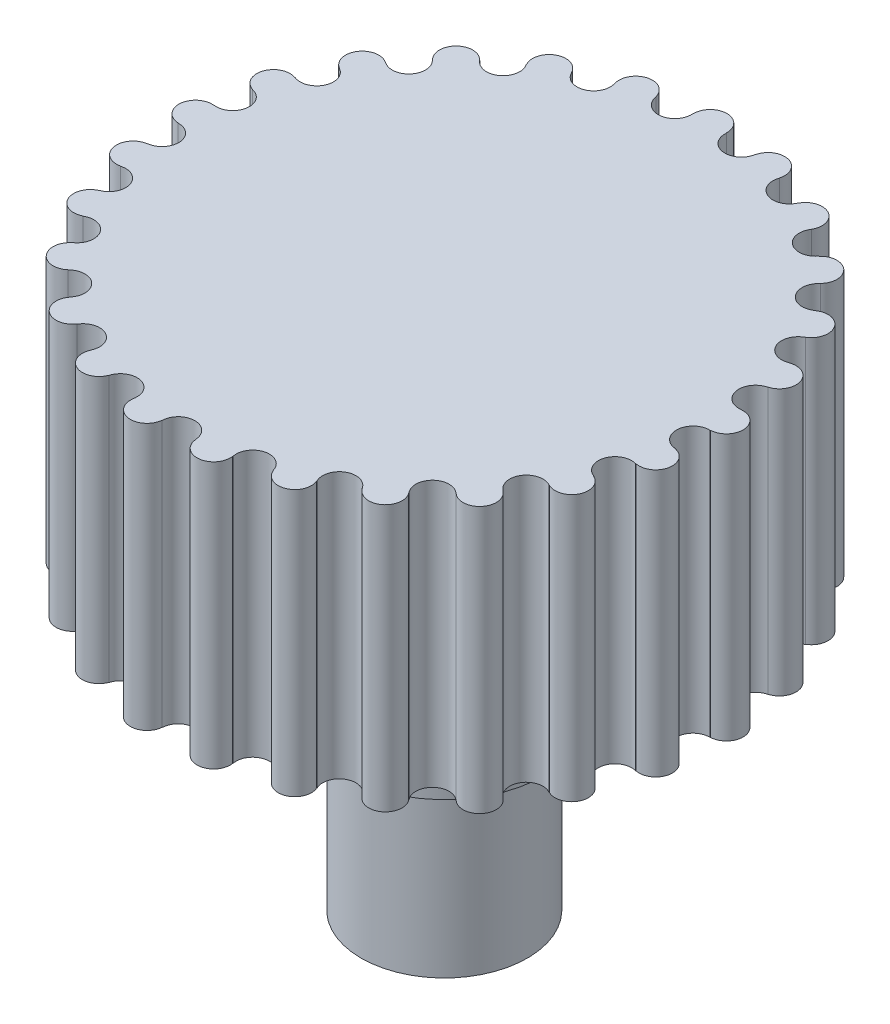
SolidWorks part; units mm, degrees
ref_plane "前视基准面" through (0, 0, 0) normal (0, 0, 1) x (1, 0, 0)
ref_plane "上视基准面" through (0, 0, 0) normal (0, 1, 0) x (1, 0, 0)
ref_plane "右视基准面" through (0, 0, 0) normal (1, 0, 0) x (0, 0, -1)
other "Configuration Table"
sketch "草图1" plane through (0, 0, 0) normal (0, 1, 0) x (1, 0, 0)
  circle A0 centre (0, 0) radius 2.5
extrude "凸台-拉伸1" add sketch "草图1" along normal blind 6
sketch "草图2" plane through (0, 6, 0) normal (0, 1, 0) x (1, 0, 0)
  circle A0 centre (0, 0) radius 3
extrude "凸台-拉伸2" add sketch "草图2" against normal blind 1
sketch "草图3" plane through (0, 6, 0) normal (0, 1, 0) x (1, 0, 0)
  circle A0 centre (0, 0) radius 2.5
extrude "凸台-拉伸3" add sketch "草图3" along normal blind 2.5
sketch "草图4" plane through (0, 8.5, 0) normal (0, 1, 0) x (1, 0, 0)
  circle A0 centre (0, 0) radius 8
extrude "凸台-拉伸4" add sketch "草图4" along normal blind 8
sketch "草图6" plane through (0, 16.5, 0) normal (0, 1, 0) x (1, 0, 0)
  circle A0 centre (0, 8) radius 0.5
  circle A1 centre (0, 0) radius 8 construction
  circle A3 centre (1.9895, 7.7487) radius 0.5
  circle A5 centre (3.854, 7.0105) radius 0.5
  circle A7 centre (5.4764, 5.8317) radius 0.5
  circle A9 centre (6.7546, 4.2866) radius 0.5
  circle A11 centre (7.6085, 2.4721) radius 0.5
  circle A13 centre (7.9842, 0.5023) radius 0.5
  circle A15 centre (7.8583, -1.4991) radius 0.5
  circle A17 centre (7.2386, -3.4062) radius 0.5
  circle A19 centre (6.1641, -5.0994) radius 0.5
  circle A21 centre (4.7023, -6.4721) radius 0.5
  circle A23 centre (2.945, -7.4382) radius 0.5
  circle A25 centre (1.0027, -7.9369) radius 0.5
  circle A27 centre (-1.0027, -7.9369) radius 0.5
  circle A29 centre (-2.945, -7.4382) radius 0.5
  circle A31 centre (-4.7023, -6.4721) radius 0.5
  circle A33 centre (-6.1641, -5.0994) radius 0.5
  circle A35 centre (-7.2386, -3.4062) radius 0.5
  circle A37 centre (-7.8583, -1.4991) radius 0.5
  circle A39 centre (-7.9842, 0.5023) radius 0.5
  circle A41 centre (-7.6085, 2.4721) radius 0.5
  circle A43 centre (-6.7546, 4.2866) radius 0.5
  circle A45 centre (-5.4764, 5.8317) radius 0.5
  circle A47 centre (-3.854, 7.0105) radius 0.5
  circle A49 centre (-1.9895, 7.7487) radius 0.5
  circle A51 centre (1.0027, 7.9369) radius 0.5 [skipped]
  circle A52 centre (2.945, 7.4382) radius 0.5 [skipped]
  circle A53 centre (4.7023, 6.4721) radius 0.5 [skipped]
  circle A54 centre (6.1641, 5.0994) radius 0.5 [skipped]
  circle A55 centre (7.2386, 3.4062) radius 0.5 [skipped]
  circle A56 centre (7.8583, 1.4991) radius 0.5 [skipped]
  circle A57 centre (7.9842, -0.5023) radius 0.5 [skipped]
  circle A58 centre (7.6085, -2.4721) radius 0.5 [skipped]
  circle A59 centre (6.7546, -4.2866) radius 0.5 [skipped]
  circle A60 centre (5.4764, -5.8317) radius 0.5 [skipped]
  circle A61 centre (3.854, -7.0105) radius 0.5 [skipped]
  circle A62 centre (1.9895, -7.7487) radius 0.5 [skipped]
  circle A63 centre (0, -8) radius 0.5 [skipped]
  circle A64 centre (-1.9895, -7.7487) radius 0.5 [skipped]
  circle A65 centre (-3.854, -7.0105) radius 0.5 [skipped]
  circle A66 centre (-5.4764, -5.8317) radius 0.5 [skipped]
  circle A67 centre (-7.6085, -2.4721) radius 0.5 [skipped]
  circle A68 centre (-6.7546, -4.2866) radius 0.5 [skipped]
  circle A69 centre (-7.9842, -0.5023) radius 0.5 [skipped]
  circle A70 centre (-7.8583, 1.4991) radius 0.5 [skipped]
  circle A71 centre (-7.2386, 3.4062) radius 0.5 [skipped]
  circle A72 centre (-6.1641, 5.0994) radius 0.5 [skipped]
  circle A73 centre (-4.7023, 6.4721) radius 0.5 [skipped]
  circle A74 centre (-2.945, 7.4382) radius 0.5 [skipped]
  circle A75 centre (-1.0027, 7.9369) radius 0.5 [skipped]
  point P105 (0, 0)
  dimension "D1" = 50
extrude "凸台-拉伸5" add sketch "草图6" against normal blind 8
sketch "草图7" plane through (0, 16.5, 0) normal (0, 1, 0) x (1, 0, 0)
  circle A0 centre (1.0027, 7.9369) radius 0.5
  circle A3 centre (2.945, 7.4382) radius 0.5
  circle A5 centre (4.7023, 6.4721) radius 0.5
  circle A7 centre (6.1641, 5.0994) radius 0.5
  circle A9 centre (7.2386, 3.4062) radius 0.5
  circle A11 centre (7.8583, 1.4991) radius 0.5
  circle A13 centre (7.9842, -0.5023) radius 0.5
  circle A15 centre (7.6085, -2.4721) radius 0.5
  circle A17 centre (6.7546, -4.2866) radius 0.5
  circle A19 centre (5.4764, -5.8317) radius 0.5
  circle A21 centre (3.854, -7.0105) radius 0.5
  circle A23 centre (1.9895, -7.7487) radius 0.5
  circle A25 centre (0, -8) radius 0.5
  circle A27 centre (-1.9895, -7.7487) radius 0.5
  circle A29 centre (-3.854, -7.0105) radius 0.5
  circle A31 centre (-5.4764, -5.8317) radius 0.5
  circle A33 centre (-6.7546, -4.2866) radius 0.5
  circle A35 centre (-7.6085, -2.4721) radius 0.5
  circle A37 centre (-7.9842, -0.5023) radius 0.5
  circle A39 centre (-7.8583, 1.4991) radius 0.5
  circle A41 centre (-7.2386, 3.4062) radius 0.5
  circle A43 centre (-6.1641, 5.0994) radius 0.5
  circle A45 centre (-4.7023, 6.4721) radius 0.5
  circle A47 centre (-2.945, 7.4382) radius 0.5
  circle A49 centre (-1.0027, 7.9369) radius 0.5
  point P103 (0, 0)
extrude "切除-拉伸1" cut sketch "草图7" against normal blind 8
sketch "草图9" plane through (0, 0, 0) normal (0, -1, 0) x (1, 0, 0)
  line L2 (-0.8441, 1.3) -> (0.8441, 1.3)
  line L3 (-0.8441, -1.3) -> (0.8441, -1.3)
  circle A1 centre (0, 0) radius 1.3 construction
  arc A3 (0.8441, -1.3) -> (0.8441, 1.3) centre (0, 0) ccw
  arc A4 (-0.8441, 1.3) -> (-0.8441, -1.3) centre (0, 0) ccw
  point P7 (0, 1.3)
  point P10 (0, -1.3)
extrude "切除-拉伸2" cut sketch "草图9" against normal blind 1.5
